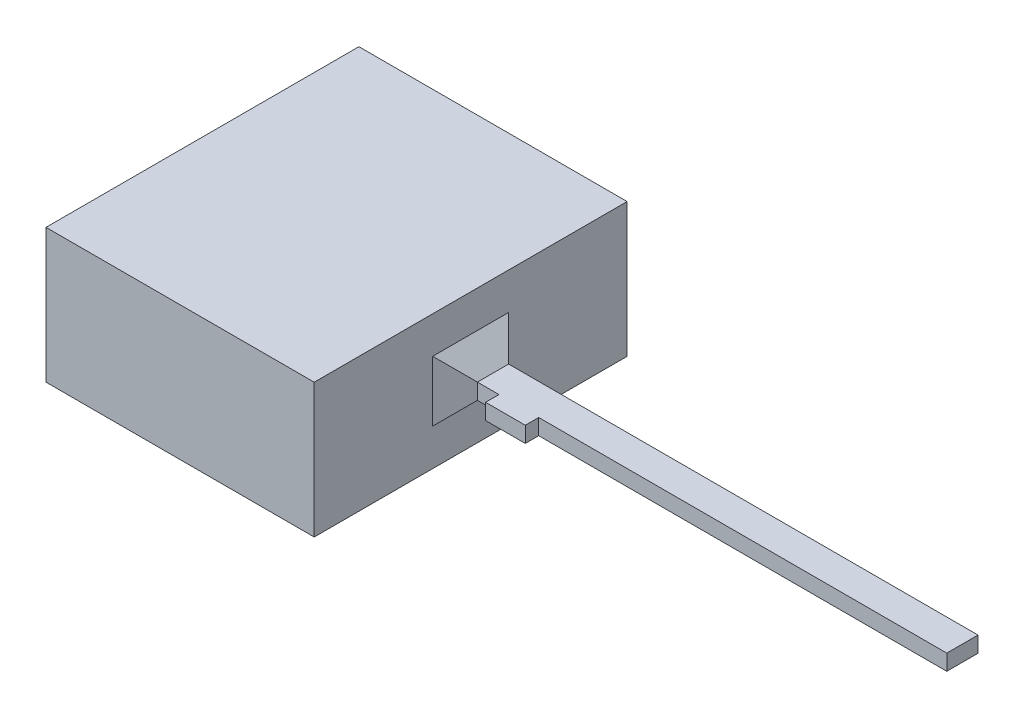
SolidWorks part; units mm, degrees
ref_plane "Front Plane" through (0, 0, 0) normal (0, 0, 1) x (1, 0, 0)
ref_plane "Top Plane" through (0, 0, 0) normal (0, 1, 0) x (1, 0, 0)
ref_plane "Right Plane" through (0, 0, 0) normal (1, 0, 0) x (0, 0, -1)
sketch "Sketch1" plane through (0, 0, 0) normal (0, 1, 0) x (1, 0, 0)
  line L1 (3, -3.5) -> (-3, -3.5)
  line L2 (3, -3.5) -> (3, 3.5)
  line L3 (3, 3.5) -> (-3, 3.5)
  line L4 (-3, -3.5) -> (-3, 3.5)
  line L5 (3, -3.5) -> (-3, 3.5) construction
  line L6 (3, 3.5) -> (-3, -3.5) construction
  point P0 (0, 0)
extrude "Boss-Extrude1" add sketch "Sketch1" along normal blind 3
sketch "Sketch2" plane through (0, 0, 0) normal (1, 0, 0) x (0, 0, -1)
  line L0 (0, 3) -> (0, 0)
  line L1 (-3.5, 3) -> (3.5, 3) construction
  line L2 (3.5, 3) -> (3.5, 0) construction
  line L3 (3.5, 1.5) -> (-3.5, 1.5)
  line L4 (-3.5, 3) -> (-3.5, 0) construction
  point P3 (0, 3)
sketch "Sketch5" plane through (3, 0, 0) normal (1, 0, 0) x (0, 0, -1)
  line L0 (0, 3) -> (0, 0) construction
  line L1 (-0.3493, 1.3233) -> (0.3493, 1.3233)
  line L2 (-0.3493, 1.3233) -> (-0.3493, 1.6767)
  line L3 (-0.3493, 1.6767) -> (0.3493, 1.6767)
  line L4 (0.3493, 1.3233) -> (0.3493, 1.6767)
  line L5 (-0.3493, 1.3233) -> (0.3493, 1.6767) construction
  line L6 (-0.3493, 1.6767) -> (0.3493, 1.3233) construction
  point P0 (0, 1.5)
extrude "Boss-Extrude3" add sketch "Sketch5" along normal blind 0.5
draft "Draft1" type of draft neutral plane draft angle 45 faces to draft 4 face at (3.25, 1.3233, 0) face at (3.25, 1.5, 0.3493) face at (3.25, 1.6767, 0) face at (3.25, 1.5, -0.3493) neutral plane through (3.5, 0, 0) neutral plane normal (1, 0, 0) parameters "D1"=45
sketch "Sketch6" plane through (3.5, 0, 0) normal (1, 0, 0) x (0, 0, -1)
  line L1 (-0.3493, 1.6767) -> (0.3493, 1.6767)
  line L2 (-0.3493, 1.6767) -> (-0.3493, 1.3233)
  line L3 (-0.3493, 1.3233) -> (0.3493, 1.3233)
  line L4 (0.3493, 1.6767) -> (0.3493, 1.3233)
extrude "Boss-Extrude4" add sketch "Sketch6" along normal blind 10.5
sketch "Sketch7" plane through (0, 1.6767, 0) normal (0, 1, 0) x (1, 0, 0)
  line L0 (3.5, 0) -> (14, 0)
  line L1 (3.5, 0.3493) -> (3.5, -0.3493) construction
  line L2 (14, 0.3493) -> (14, -0.3493) construction
sketch "Sketch8" plane through (14, 0, 0) normal (1, 0, 0) x (0, 0, -1)
  line L0 (0, 1.6767) -> (0, 1.3233)
  line L1 (0.3493, 1.6767) -> (-0.3493, 1.6767) construction
  line L2 (-0.3493, 1.3233) -> (0.3493, 1.3233) construction
sketch3d "3DSketch1"
  line L0 (3.5, 1.6767, 0) -> (14, 1.6767, 0) construction
  line L1 (14, 1.6767, 0) -> (14, 1.3233, 0) construction
sketch "Sketch9" plane through (0, 0, 0.3493) normal (0, 0, 1) x (1, 0, 0)
  line L0 (3.5, 1.6767) -> (14, 1.6767) construction
  line L1 (3.9828, 1.6767) -> (4.8715, 1.6767)
  line L2 (3.9828, 1.6767) -> (3.9828, 1.3233)
  line L3 (3.9828, 1.3233) -> (4.8715, 1.3233)
  line L4 (4.8715, 1.6767) -> (4.8715, 1.3233)
  line L5 (14, 1.3233) -> (3.5, 1.3233) construction
extrude "Boss-Extrude5" add sketch "Sketch9" along normal blind 0.3 contours L2 L3 L4 L1
